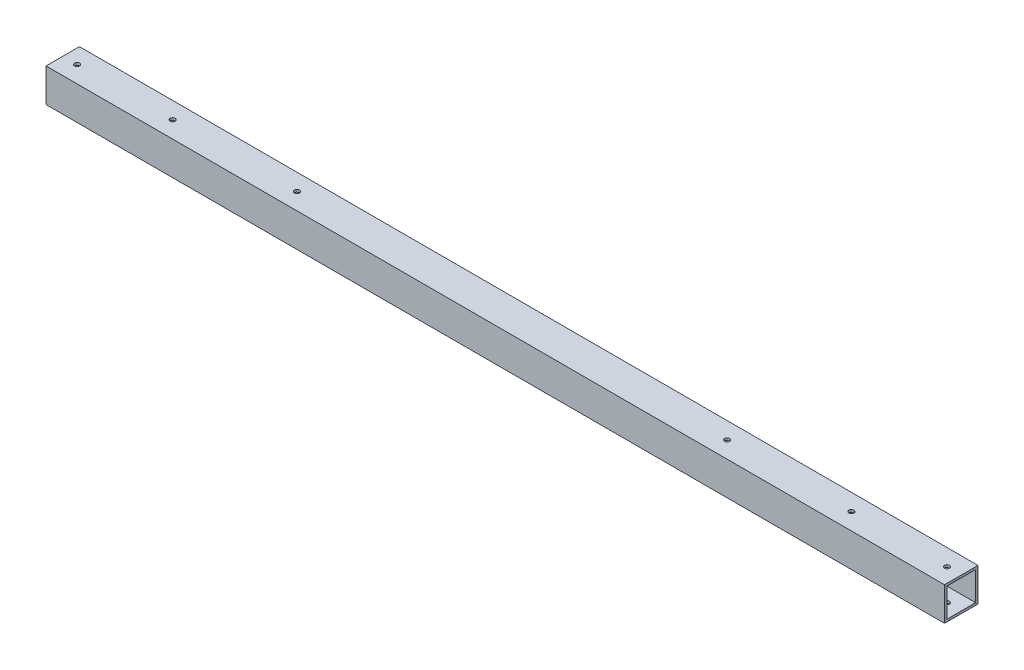
SolidWorks part; units mm, degrees
material "6061 Alloy"
ref_plane "Front Plane" through (0, 0, 0) normal (0, 0, 1) x (1, 0, 0)
ref_plane "Top Plane" through (0, 0, 0) normal (0, 1, 0) x (1, 0, 0)
ref_plane "Right Plane" through (0, 0, 0) normal (1, 0, 0) x (0, 0, -1)
sketch "Sketch1" plane through (0, 0, 0) normal (1, 0, 0) x (0, 0, -1)
  line L0 (-19.05, -19.05) -> (19.05, -19.05)
  line L1 (-22.225, -22.225) -> (22.225, -22.225)
  line L2 (-22.225, -22.225) -> (-22.225, 22.225)
  line L3 (-22.225, 22.225) -> (22.225, 22.225)
  line L4 (22.225, -22.225) -> (22.225, 22.225)
  line L5 (-22.225, -22.225) -> (22.225, 22.225) construction
  line L6 (-22.225, 22.225) -> (22.225, -22.225) construction
  line L7 (19.05, -19.05) -> (19.05, 19.05)
  line L8 (-19.05, 19.05) -> (19.05, 19.05)
  line L9 (-19.05, -19.05) -> (-19.05, 19.05)
  point P0 (0, 0)
  dimension "D1" = 44.45
  dimension "D2" = 3.175
extrude "Boss-Extrude1" add sketch "Sketch1" along normal blind 1193.8
hole_wizard "1/4 Clearance Hole1" positions "Sketch2" profile "Sketch3" hole size "1/4" standard "ANSI Inch" end condition through all
sketch "Sketch2" plane through (0, 22.225, 0) normal (0, 1, 0) x (1, 0, 0)
  line L0 (596.9, -22.225) -> (596.9, 22.225) construction
  line L1 (1193.8, -22.225) -> (0, -22.225) construction
  line L2 (1193.8, 22.225) -> (0, 22.225) construction
  line L3 (0, 0) -> (1193.8, 0) construction
  line L4 (1193.8, 22.225) -> (1193.8, -22.225) construction
  line L5 (0, 22.225) -> (0, -22.225) construction
  point P0 (311.15, 0)
  point P2 (146.05, 0)
  point P4 (19.05, 0)
  point P14 (1174.75, 0)
  point P15 (1047.75, 0)
  point P16 (882.65, 0)
  point P23 (463.5637, 0)
  point P24 (292.7266, 0)
  point P25 (160.7792, 0)
  dimension "D1" = 571.5
  dimension "D2" = 146.05
  dimension "D3" = 19.05
sketch "Sketch3" plane through (311.15, 22.225, 0) normal (1, 0, 0) x (0, 0, 1)
  line L0 (0, 0) -> (0, 44.45)
  line L1 (0, 44.45) -> (3.3782, 44.45)
  line L2 (3.3782, 44.45) -> (3.3782, 0)
  line L5 (3.3782, 0) -> (0, 0)
  line L11 (0, -6.35) -> (0, 107.95) construction
  dimension "Thru Hole Dia." = 6.7564
  dimension "Thru Hole Depth" = 44.45
